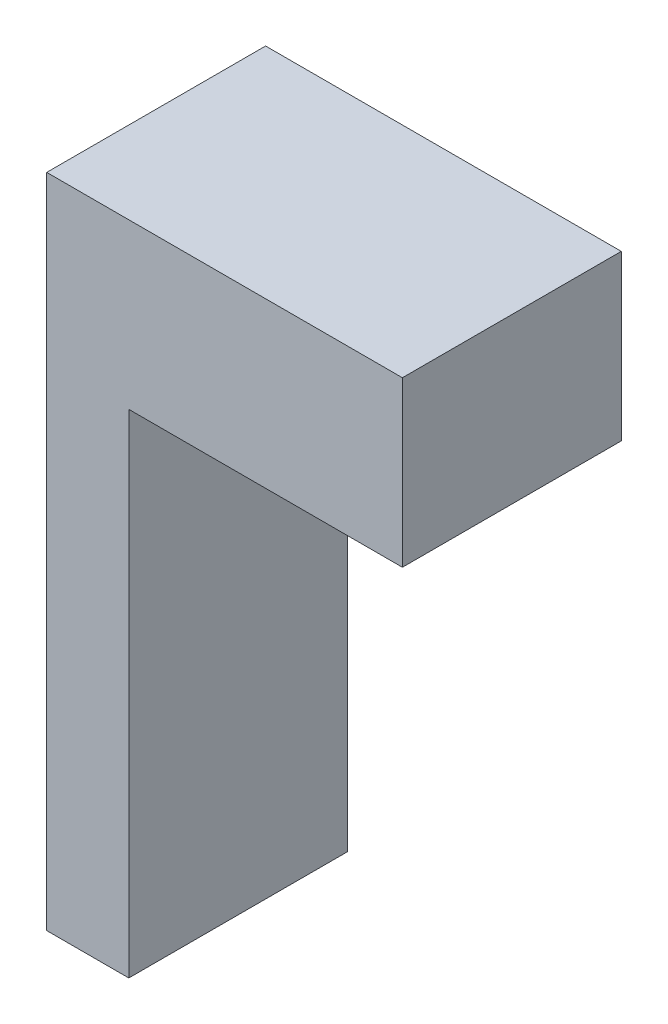
SolidWorks part; units mm, degrees
ref_plane "Plan de face" through (0, 0, 0) normal (0, 0, 1) x (1, 0, 0)
ref_plane "Plan de dessus" through (0, 0, 0) normal (0, 1, 0) x (1, 0, 0)
ref_plane "Plan de droite" through (0, 0, 0) normal (1, 0, 0) x (0, 0, -1)
sketch "Esquisse1" plane through (0, 0, 0) normal (0, 0, 1) x (1, 0, 0)
  line L0 (0, 0) -> (50, 0)
  line L1 (50, 0) -> (50, 30)
  line L2 (50, 30) -> (-15, 30)
  line L3 (-15, 30) -> (-15, -90)
  line L4 (-15, -90) -> (0, -90)
  line L5 (0, -90) -> (0, 0)
  dimension "D1" = 50
  dimension "D2" = 90
  dimension "D3" = 30
  dimension "D4" = 15
extrude "Boss.-Extru.1" add sketch "Esquisse1" along normal blind 40
